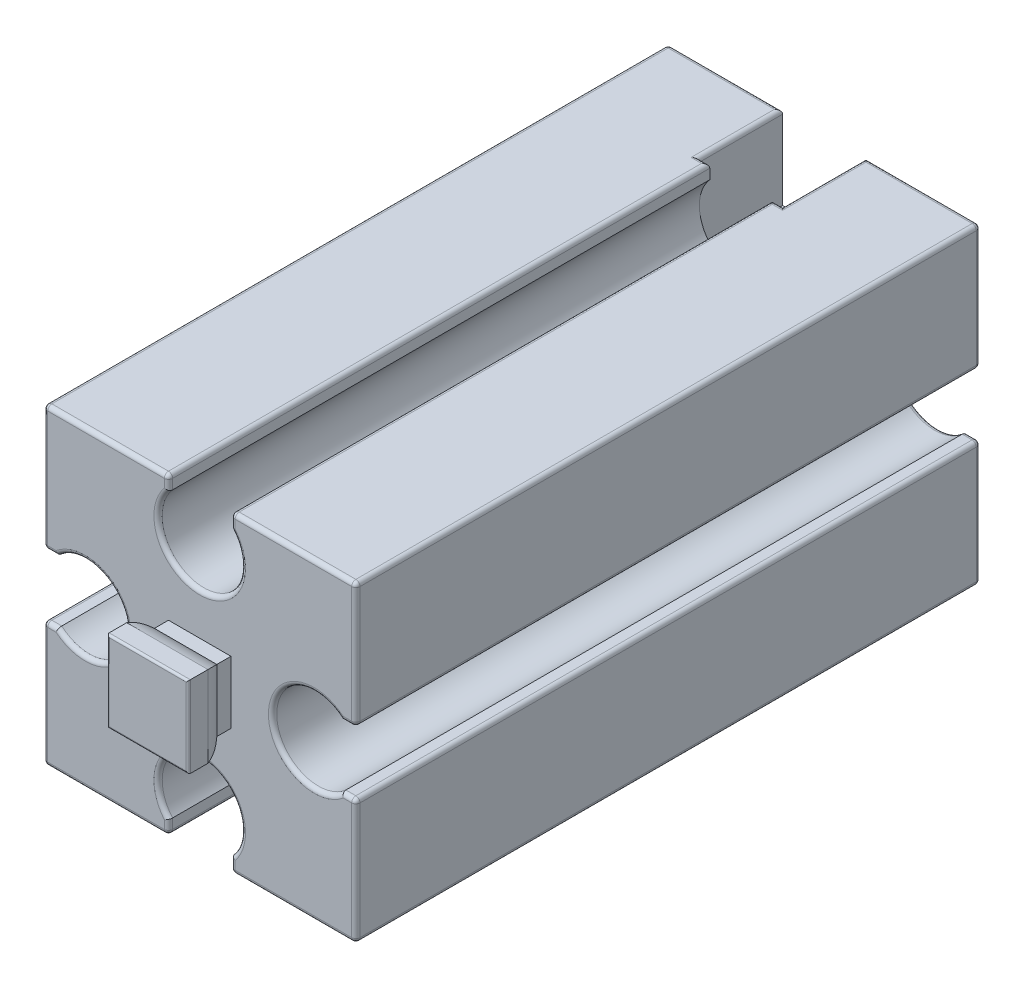
SolidWorks part; units mm, degrees
ref_plane "前视基准面" through (0, 0, 0) normal (0, 0, 1) x (1, 0, 0)
ref_plane "上视基准面" through (0, 0, 0) normal (0, 1, 0) x (1, 0, 0)
ref_plane "右视基准面" through (0, 0, 0) normal (1, 0, 0) x (0, 0, -1)
sketch "草图1" plane through (0, 0, 0) normal (0, 0, 1) x (1, 0, 0)
  line L1 (-7.5, -7.5) -> (7.5, -7.5)
  line L2 (-7.5, -7.5) -> (-7.5, 7.5)
  line L3 (-7.5, 7.5) -> (7.5, 7.5)
  line L4 (7.5, -7.5) -> (7.5, 7.5)
extrude "凸台-拉伸1" add sketch "草图1" against normal blind 30
sketch "草图2" plane through (0, 0, 0) normal (0, 1, 0) x (1, 0, 0)
  line L0 (-7.5, 0) -> (7.5, 0) construction
  line L1 (-1.5, 0) -> (1.5, 0)
  line L2 (-1.5, 0) -> (-1.5, -1)
  line L3 (-1.5, -1) -> (1.5, -1)
  line L4 (1.5, 0) -> (1.5, -1)
extrude "凸台-拉伸2" add sketch "草图2" along normal blind 1.5 and the other way blind 1.5
sketch "草图3" plane through (0, 0, 0) normal (0, 1, 0) x (1, 0, 0)
  line L1 (-1.95, -2.5) -> (1.95, -2.5)
  line L2 (-1.95, -2.5) -> (-1.95, -1.5556)
  line L3 (1.95, -2.5) -> (1.95, -1.5556)
  line L4 (-1.5, 0) -> (-1.5, -1) construction
  line L5 (-1.5, -0.6771) -> (1.5, -0.6771)
  arc A0 (-1.5, -0.6771) -> (-1.95, -1.5556) centre (0, -2) ccw
  arc A1 (1.95, -1.5556) -> (1.5, -0.6771) centre (0, -2) ccw
extrude "凸台-拉伸3" add sketch "草图3" along normal blind 3 and the other way blind 3
sketch "草图5" plane through (0, 0, 0) normal (0, 0, 1) x (1, 0, 0)
  line L0 (-7.5, -7.5) -> (7.5, -7.5) construction
  line L1 (-1.5, -7.5) -> (1.5, -7.5)
  line L2 (-1.5, -7.5) -> (-1.5, -6.8229)
  line L3 (-7.5, 7.5) -> (-7.5, -7.5) construction
  line L4 (1.5, -7.5) -> (1.5, -6.8229)
  line L6 (1.5, 7.5) -> (1.5, 6.8229)
  line L7 (-1.5, 7.5) -> (-1.5, 6.8229)
  line L8 (-1.5, 7.5) -> (1.5, 7.5)
  line L9 (-7.5, 1.5) -> (-6.8229, 1.5)
  line L10 (-7.5, 1.5) -> (-7.5, -1.5)
  line L11 (-7.5, -1.5) -> (-6.8229, -1.5)
  line L12 (7.5, -1.5) -> (6.8229, -1.5)
  line L13 (7.5, 1.5) -> (7.5, -1.5)
  line L14 (7.5, 1.5) -> (6.8229, 1.5)
  arc A0 (1.5, -6.8229) -> (-1.5, -6.8229) centre (0, -5.5) ccw
  arc A1 (1.5, 6.8229) -> (-1.5, 6.8229) centre (0, 5.5) cw
  arc A2 (-6.8229, -1.5) -> (-6.8229, 1.5) centre (-5.5, 0) ccw
  arc A3 (6.8229, -1.5) -> (6.8229, 1.5) centre (5.5, 0) cw
extrude "切除-拉伸2" cut sketch "草图5" against normal through all
sketch "草图6" plane through (0, 7.5, 0) normal (0, 1, 0) x (-1, 0, 0)
  line L0 (1.5, -30) -> (7.5, -30) construction
  line L1 (2, -30) -> (-2, -30)
  line L2 (2, -30) -> (2, -26)
  line L3 (2, -26) -> (-2, -26)
  line L4 (-2, -30) -> (-2, -26)
extrude "切除-拉伸3" cut sketch "草图6" against normal blind 4
sketch "草图9" plane through (0, -7.5, 0) normal (0, -1, 0) x (1, 0, 0)
  line L0 (-7.5, -30) -> (-1.5, -30) construction
  line L1 (-2, -30) -> (2, -30)
  line L2 (-2, -30) -> (-2, -26)
  line L3 (-2, -26) -> (2, -26)
  line L4 (2, -30) -> (2, -26)
extrude "切除-拉伸5" cut sketch "草图9" against normal blind 4
sketch "草图11" plane through (0, 0, 0) normal (0, 1, 0) x (1, 0, 0)
  line L0 (2, 30) -> (-2, 30) construction
  line L1 (-1.5, 30) -> (1.5, 30)
  line L2 (-1.5, 30) -> (-1.5, 29.3229)
  line L4 (1.5, 30) -> (1.5, 29.3229)
  arc A0 (-1.5, 29.3229) -> (1.5, 29.3229) centre (0, 28) ccw
extrude "切除-拉伸6" cut sketch "草图11" against normal through all and the other way through all
sketch "草图12" plane through (0, 0, 0) normal (1, 0, 0) x (0, 0, -1)
  line L0 (-2.5, 3) -> (-2.5, 1.95)
  line L1 (-2.5, 1.95) -> (-1.5556, 1.95)
  line L2 (-2.5, -1.95) -> (-1.5556, -1.95)
  line L5 (-2.5, -1.95) -> (-2.5, -3)
  line L6 (-2.5, 3) -> (-0.6771, 3)
  line L7 (-0.6771, 3) -> (-0.6771, 1.5)
  line L8 (-2.5, -3) -> (-0.6771, -3)
  line L9 (-0.6771, -3) -> (-0.6771, -1.5)
  arc A0 (-0.6771, 1.5) -> (-1.5556, 1.95) centre (-2, 0) ccw
  arc A1 (-1.5556, -1.95) -> (-0.6771, -1.5) centre (-2, 0) ccw
extrude "切除-拉伸7" cut sketch "草图12" against normal up to next and the other way up to next
fillet "圆角2" radius 0.1 4 edges at (-1.95, 0, 2.5) (0, -1.95, 2.5) (1.95, 0, 2.5) (0, 1.95, 2.5)
fillet "圆角3" radius 0.2 54 edges at (-4.75, 7.5, -30) (-7.5, 4.5, -30) (-7.1614, 1.5, -30) (-3.5, 0, -30) (-7.1614, -1.5, -30) (-7.5, -4.5, -30) (-4.75, -7.5, -30) (4.75, -7.5, -30) (7.5, -4.5, -30) (7.1614, -1.5, -30) (3.5, 0, -30) (7.1614, 1.5, -30) (7.5, 4.5, -30) (4.75, 7.5, -30) (7.1614, -1.5, 0) (7.5, -4.5, 0) (4.5, -7.5, 0) (1.5, -7.1614, 0) (0, -3.5, 0) (-1.5, -7.1614, 0) (-4.5, -7.5, 0) (-7.5, -4.5, 0) (-7.1614, -1.5, 0) (-3.5, 0, 0) (-7.1614, 1.5, 0) (-7.5, 4.5, 0) (-4.5, 7.5, 0) (-1.5, 7.1614, 0) (0, 3.5, 0) (1.5, 7.1614, 0) (4.5, 7.5, 0) (7.5, 4.5, 0) (7.1614, 1.5, 0) (3.5, 0, 0) (-7.5, -7.5, -15) (-1.5, -7.5, -13) (-1.75, -7.5, -26) (-2, -7.5, -28) (1.5, -7.5, -13) (7.5, -7.5, -15) (2, -7.5, -28) (1.75, -7.5, -26) (7.5, 7.5, -15) (1.5, 7.5, -13) (1.75, 7.5, -26) (2, 7.5, -28) (-1.75, 7.5, -26) (-1.5, 7.5, -13) (-7.5, 7.5, -15) (-2, 7.5, -28) (-7.5, 1.5, -15) (-7.5, -1.5, -15) (7.5, -1.5, -15) (7.5, 1.5, -15)
